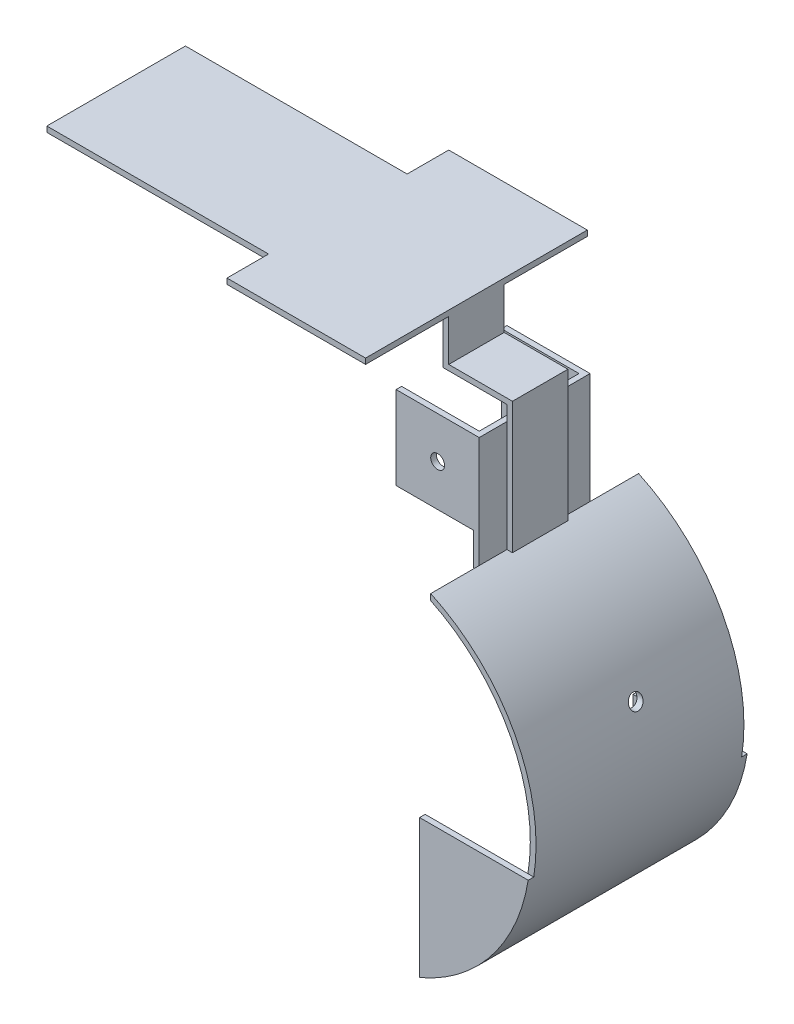
SolidWorks part; units mm, degrees
ref_plane "Front Plane" through (0, 0, 0) normal (0, 0, 1) x (1, 0, 0)
ref_plane "Top Plane" through (0, 0, 0) normal (0, 1, 0) x (1, 0, 0)
ref_plane "Right Plane" through (0, 0, 0) normal (1, 0, 0) x (0, 0, -1)
sketch "Sketch1" plane through (0, 0, 0) normal (0, 0, 1) x (1, 0, 0)
  line L0 (13, -144.9833) -> (12.135, -143.18)
  line L1 (-15, -15) -> (15, -15)
  line L2 (-15, -15) -> (-15, 15)
  line L3 (-15, 15) -> (15, 15)
  line L4 (15, -15) -> (15, 15)
  line L5 (-15, -15) -> (15, 15) construction
  line L6 (-15, 15) -> (15, -15) construction
  line L7 (15, -15) -> (13, -15)
  line L8 (15, -15) -> (15, -25)
  line L9 (15, -25) -> (13, -25)
  line L10 (13, -15) -> (13, -25)
  line L11 (13, -85.6418) -> (53, -85.6418)
  line L12 (13, -27) -> (13, -25)
  line L13 (14.1579, -26.8141) -> (13, -26.8141)
  line L14 (15, -25) -> (14.1579, -26.8141)
  line L15 (13, -26.8141) -> (13, -25)
  arc A0 (15, -25) -> (13, -144.9833) centre (-12.641, -84.5476) cw
  arc A1 (14.1579, -26.8141) -> (12.135, -143.18) centre (-12.7809, -84.5463) cw
  point P0 (0, 0)
  dimension "D1" = 30
  dimension "D2" = 30
  dimension "D3" = 10
  dimension "D4" = 2
  dimension "D5" = 120
  dimension "D6" = 40
  dimension "D7" = 2
  dimension "D8" = 2
  dimension "D9" = 2
extrude "Boss-Extrude1" add sketch "Sketch1" along normal blind 75 contours L1 L4 L3 L2 | L14 A1 L11 A0 | L1 L10 L9 L8 | L14 L9 L12 L13 | L11 A1 L0 A0
ref_plane "Plane1" through (0, 15, 0) normal (0, 1, 0) x (1, 0, 0)
sketch "Sketch2" plane through (0, 15, 0) normal (0, 1, 0) x (1, 0, 0)
  line L0 (-15, -37.5) -> (15, -37.5)
  line L1 (-15, -75) -> (-15, 0) construction
  line L2 (15, -75) -> (15, 0) construction
  line L3 (-15, -75) -> (15, -75) construction
  line L4 (-15, -57.5) -> (15, -57.5)
  line L5 (-15, -57.5) -> (-15, -17.5)
  line L6 (-15, -17.5) -> (15, -17.5)
  line L7 (15, -57.5) -> (15, -17.5)
  line L8 (-15, -57.5) -> (15, -17.5) construction
  line L9 (-15, -17.5) -> (15, -57.5) construction
  line L10 (-15, 0) -> (15, 0)
  line L11 (-15, 0) -> (-15, -17.5)
  line L12 (-15, -17.5) -> (15, -17.5)
  line L13 (15, 0) -> (15, -17.5)
  line L14 (-15, -57.5) -> (15, -57.5)
  line L15 (-15, -57.5) -> (-15, -75)
  line L16 (-15, -75) -> (15, -75)
  line L17 (15, -57.5) -> (15, -75)
  line L19 (-15, -57.5) -> (15, -57.5)
  line L20 (-15, -57.5) -> (-15, -75)
  line L21 (-15, -75) -> (15, -75)
  line L22 (15, -57.5) -> (15, -75)
  point P6 (0, -37.5)
  dimension "D1" = 40
extrude "Cut-Extrude1" cut sketch "Sketch2" against normal blind 75 contours L13 L10 L11 L6 | L17 L4 L15 L16
ref_plane "Plane2" through (-15, 0, 0) normal (-1, 0, 0) x (0, 0, 1)
sketch "Sketch3" plane through (-15, 0, 0) normal (-1, 0, 0) x (0, 0, 1)
  line L0 (37.5, -15) -> (37.5, 15.0607)
  line L1 (57.5, -15) -> (17.5, -15) construction
  line L2 (17.5, -15) -> (17.5, 15) construction
  line L3 (19.5, -15.051) -> (55.5, -15.051)
  line L4 (19.5, -15.051) -> (19.5, 15.1117)
  line L5 (19.5, 15.1117) -> (55.5, 15.1117)
  line L6 (55.5, -15.051) -> (55.5, 15.1117)
  line L7 (19.5, -15.051) -> (55.5, 15.1117) construction
  line L8 (19.5, 15.1117) -> (55.5, -15.051) construction
  point P4 (37.5, 0.0303)
  dimension "D1" = 2
extrude "Cut-Extrude2" cut sketch "Sketch3" against normal blind 28
sketch "Sketch4" plane through (0, 0, 57.5) normal (0, 0, 1) x (1, 0, 0)
  line L0 (-15, 0) -> (15, 0)
  line L1 (-15, -15) -> (-15, 15) construction
  line L2 (15, -25) -> (15, 15) construction
ref_plane "Plane3" through (0, 0, 57.5) normal (0, 0, 1) x (1, 0, 0)
sketch "Sketch5" plane through (0, 0, 57.5) normal (0, 0, 1) x (1, 0, 0)
  circle A0 centre (0, 0) radius 2.5
  dimension "D1" = 5
extrude "Cut-Extrude3" cut sketch "Sketch5" against normal blind 50
ref_plane "Plane4" through (0, 0, 75) normal (0, 0, 1) x (1, 0, 0)
sketch "Sketch6" plane through (0, 0, 75) normal (0, 0, 1) x (1, 0, 0)
  line L0 (13, -144.9833) -> (13, -94.9833)
  line L1 (13, -94.9833) -> (52.1744, -94.9833)
  arc A0 (13, -144.9833) -> (15, -25) centre (-12.641, -84.5476) ccw construction
  arc A1 (52.1744, -94.9833) -> (13, -144.9833) centre (-12.641, -84.5476) cw
  dimension "D1" = 50
extrude "Boss-Extrude2" add sketch "Sketch6" along normal blind 2
ref_plane "Plane5" through (0, 0, 0) normal (0, 0, -1) x (-1, 0, 0)
sketch "Sketch7" plane through (0, 0, 0) normal (0, 0, -1) x (-1, 0, 0)
  line L0 (-13, -144.9833) -> (-13, -94.9833)
  line L1 (-13, -94.9833) -> (-52.1744, -94.9833)
  arc A0 (-15, -25) -> (-13, -144.9833) centre (12.641, -84.5476) ccw construction
  arc A1 (-52.1744, -94.9833) -> (-13, -144.9833) centre (12.641, -84.5476) ccw
  dimension "D1" = 50
extrude "Boss-Extrude3" add sketch "Sketch7" along normal blind 2
ref_plane "Plane6" through (10.46, 0, 0) normal (-1, 0, 0) x (0, 0, 1)
sketch "Sketch9" plane through (13, 0, 0) normal (-1, 0, 0) x (0, 0, 1)
  line L0 (17.5, -26.8141) -> (52.5, -26.8141)
  line L1 (57.5, -26.8141) -> (17.5, -26.8141) construction
  line L2 (35, -26.8141) -> (35, -61.8141)
  circle A0 centre (35, -61.8141) radius 2.5
  point P8 (0, 0)
  dimension "D2" = 5
  dimension "D1" = 35
extrude "Cut-Extrude4" cut sketch "Sketch9" against normal through all
ref_plane "Plane8" through (15, 0, 0) normal (1, 0, 0) x (0, 0, -1)
sketch "Sketch11" plane through (15, 0, 0) normal (1, 0, 0) x (0, 0, -1)
  line L0 (-37.5, -25) -> (-37.5, 15.3388)
  line L1 (-57.5, -25) -> (-17.5, -25) construction
  line L3 (-27.5, 15.3388) -> (-47.5, 15.3388)
  line L4 (-27.5, 15.3388) -> (-27.5, -25)
  line L5 (-27.5, -25) -> (-47.5, -25)
  line L6 (-47.5, 15.3388) -> (-47.5, -25)
  line L7 (-27.5, 15.3388) -> (-47.5, -25) construction
  line L8 (-27.5, -25) -> (-47.5, 15.3388) construction
  line L9 (-27.5, 15.3388) -> (-47.5, 15.3388)
  line L10 (-27.5, 15.3388) -> (-27.5, 20.3388)
  line L11 (-27.5, 20.3388) -> (-47.5, 20.3388)
  line L12 (-47.5, 15.3388) -> (-47.5, 20.3388)
  point P4 (-37.5, -4.8306)
  dimension "D1" = 20
  dimension "D2" = 5
extrude "Boss-Extrude4" add sketch "Sketch11" along normal blind 2 contours L3 L6 L5 L0 | L5 L4 L3 L0 | L12 L3 L10 L11
ref_plane "Plane9" through (0, 20.3388, 0) normal (0, 1, 0) x (1, 0, 0)
sketch "Sketch13" plane through (0, 20.3388, 0) normal (0, 1, 0) x (1, 0, 0)
  line L1 (17, -47.5) -> (-8, -47.5)
  line L2 (17, -47.5) -> (17, -27.5)
  line L3 (17, -27.5) -> (-8, -27.5)
  line L4 (-8, -47.5) -> (-8, -27.5)
  dimension "D1" = 25
extrude "Boss-Extrude5" add sketch "Sketch13" along normal blind 2
ref_plane "Plane10" through (0, 22.3388, 0) normal (0, 1, 0) x (1, 0, 0)
sketch "Sketch15" plane through (0, 22.3388, 0) normal (0, 1, 0) x (1, 0, 0)
  line L0 (17, -27.5) -> (-8, -27.5) construction
  line L1 (-8, -47.5) -> (-6, -47.5)
  line L2 (-8, -47.5) -> (-8, -27.5)
  line L3 (-8, -27.5) -> (-6, -27.5)
  line L4 (-6, -47.5) -> (-6, -27.5)
  dimension "D1" = 2
extrude "Boss-Extrude6" add sketch "Sketch15" along normal blind 15
ref_plane "Plane11" through (0, 37.3388, 0) normal (0, 1, 0) x (1, 0, 0)
sketch "Sketch16" plane through (0, 37.3388, 0) normal (0, 1, 0) x (1, 0, 0)
  line L0 (-6, -37.5) -> (-56, -37.5)
  line L1 (-6, -47.5) -> (-6, -27.5) construction
  line L3 (-6, -77.5) -> (-56, -77.5)
  line L4 (-6, -77.5) -> (-6, 2.5)
  line L5 (-6, 2.5) -> (-56, 2.5)
  line L6 (-56, -77.5) -> (-56, 2.5)
  line L7 (-6, -77.5) -> (-56, 2.5) construction
  line L8 (-6, 2.5) -> (-56, -77.5) construction
  line L9 (-56, -12.5) -> (-136, -12.5)
  line L10 (-56, -12.5) -> (-56, -37.5)
  line L11 (-56, -37.5) -> (-136, -37.5)
  line L12 (-136, -12.5) -> (-136, -37.5)
  line L13 (-136, -37.5) -> (-56, -37.5)
  line L14 (-136, -37.5) -> (-136, -62.5)
  line L15 (-136, -62.5) -> (-56, -62.5)
  line L16 (-56, -37.5) -> (-56, -62.5)
  point P4 (-31, -37.5)
  dimension "D1" = 50
  dimension "D2" = 80
  dimension "D3" = 80
  dimension "D4" = 25
  dimension "D5" = 25
extrude "Boss-Extrude8" add sketch "Sketch16" along normal blind 2 contours L14 L15 L6 L11 | L9 L12 L11 L6 | L6 L3 L4 L0 | L6 L0 L4 L5
